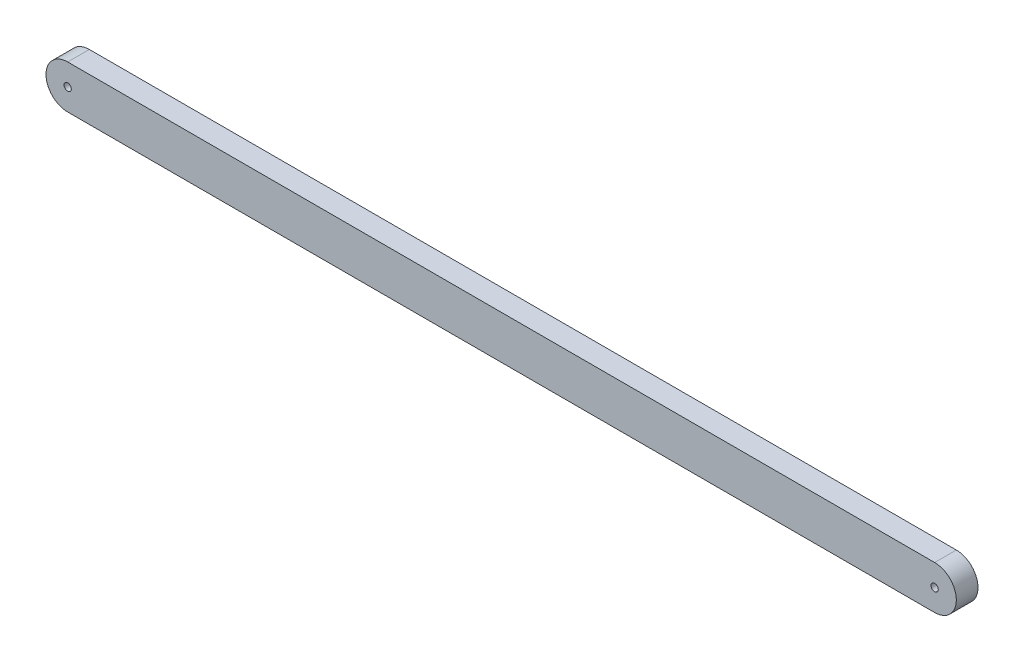
SolidWorks part; units mm, degrees
ref_plane "Front Plane" through (0, 0, 0) normal (0, 0, 1) x (1, 0, 0)
ref_plane "Top Plane" through (0, 0, 0) normal (0, 1, 0) x (1, 0, 0)
ref_plane "Right Plane" through (0, 0, 0) normal (1, 0, 0) x (0, 0, -1)
sketch "Sketch2" plane through (0, 0, 0) normal (0, 0, 1) x (1, 0, 0)
  line L0 (0, 0) -> (120, 0) construction
  line L1 (0, 3) -> (120, 3)
  line L2 (0, -3) -> (120, -3)
  arc A0 (0, 3) -> (0, -3) centre (0, 0) ccw
  arc A1 (120, -3) -> (120, 3) centre (120, 0) ccw
  circle A2 centre (0, 0) radius 0.5
  circle A3 centre (120, 0) radius 0.5
  point P3 (60, 0)
  dimension "D2" = 1
  dimension "D3" = 1
  dimension "D1" = 120
  dimension "D4" = 6
extrude "Boss-Extrude1" add sketch "Sketch2" along normal blind 3
